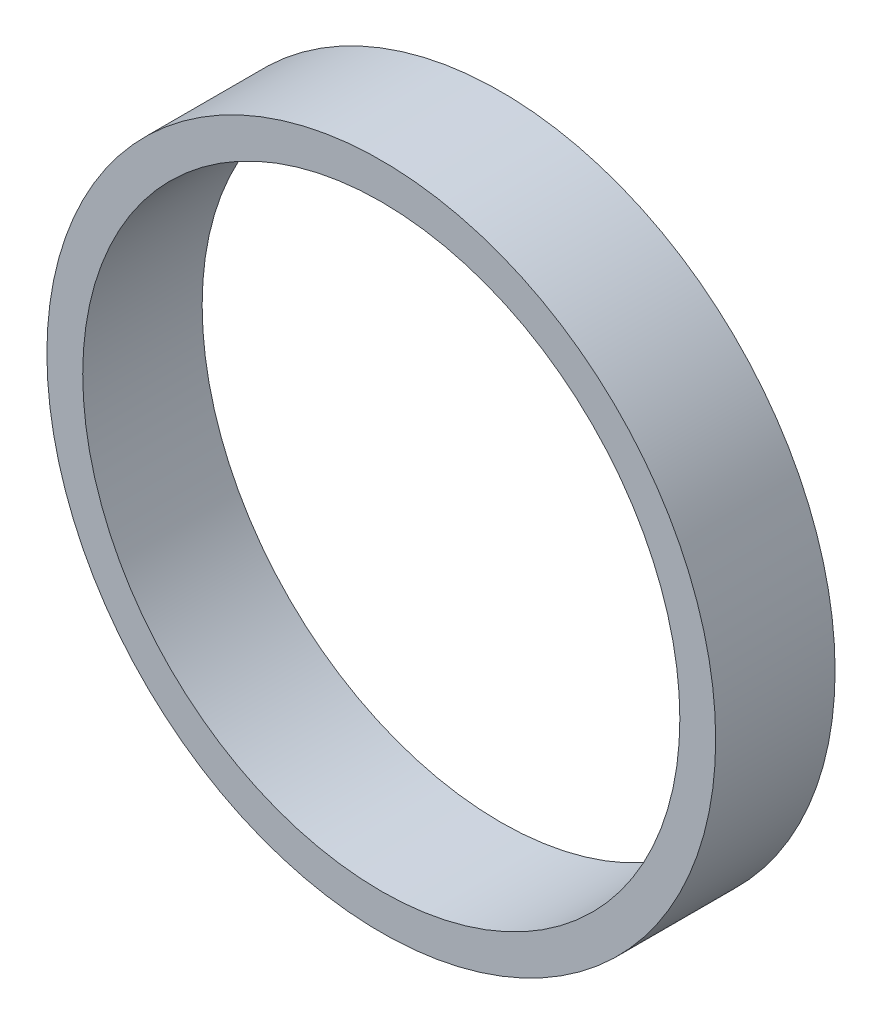
SolidWorks part; units mm, degrees
material "1.0050 (E295)"
ref_plane "Front Plane" through (0, 0, 0) normal (0, 0, 1) x (1, 0, 0)
ref_plane "Top Plane" through (0, 0, 0) normal (0, 1, 0) x (1, 0, 0)
ref_plane "Right Plane" through (0, 0, 0) normal (1, 0, 0) x (0, 0, -1)
sketch "Sketch1" plane through (0, 0, 0) normal (0, 0, 1) x (1, 0, 0)
  circle A0 centre (0, 0) radius 25
  circle A1 centre (0, 0) radius 28
  dimension "D1" = 50
  dimension "D2" = 56
extrude "Boss-Extrude1" add sketch "Sketch1" along normal blind 10
